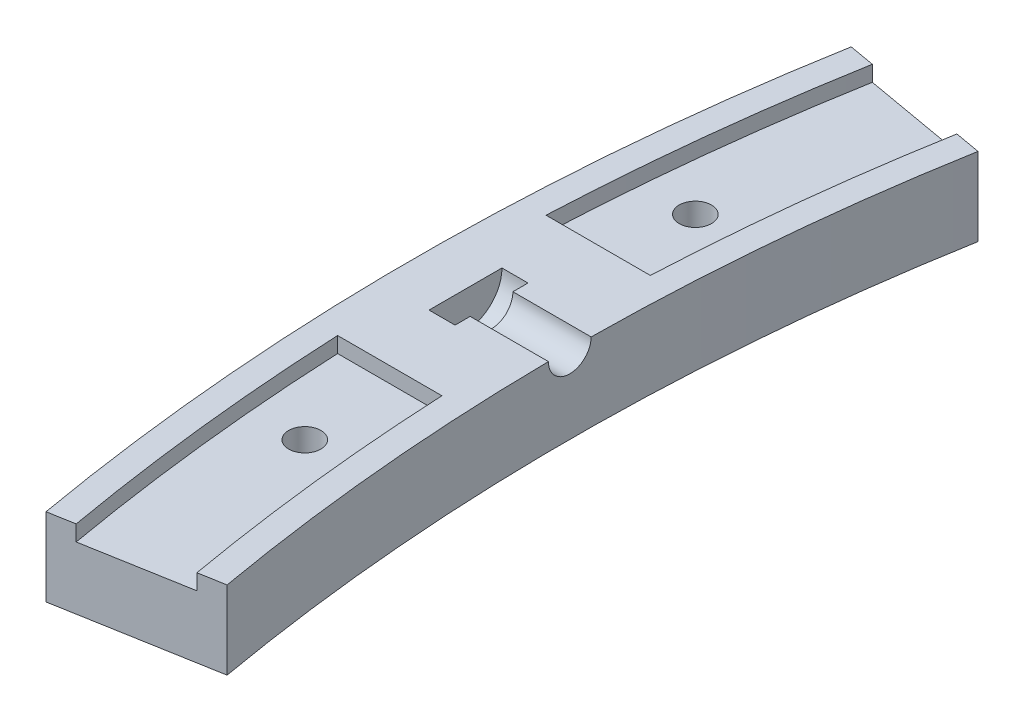
SolidWorks part; units mm, degrees
ref_plane "Front Plane" through (0, 0, 0) normal (0, 0, 1) x (1, 0, 0)
ref_plane "Top Plane" through (0, 0, 0) normal (0, 1, 0) x (1, 0, 0)
ref_plane "Right Plane" through (0, 0, 0) normal (1, 0, 0) x (0, 0, -1)
sketch "Sketch1" plane through (0, 0, 0) normal (0, 1, 0) x (1, 0, 0)
  line L0 (0, 0) -> (-219.1197, -38.6367) construction
  line L1 (0, 0) -> (-219.1197, 38.6367) construction
  line L2 (0, 0) -> (-215, 0) construction
  line L3 (-219.1197, 38.6367) -> (-204.3476, 36.032)
  line L4 (-204.3476, -36.032) -> (-219.1197, -38.6367)
  arc A0 (-216.6577, 38.2026) -> (-216.6577, -38.2026) centre (0, 0) ccw construction
  arc A1 (-206.8096, 36.4661) -> (-206.8096, -36.4661) centre (0, 0) ccw construction
  arc A2 (-211.7337, -37.3344) -> (-211.7337, 37.3344) centre (0, 0) cw construction
  arc A3 (-219.1197, 38.6367) -> (-219.1197, -38.6367) centre (0, 0) ccw
  arc A4 (-204.3476, 36.032) -> (-204.3476, -36.032) centre (0, 0) ccw
  dimension "D1" = 220
  dimension "D2" = 210
  dimension "D3" = 5
  dimension "D5" = 2.5
  dimension "D6" = 2.5
  dimension "D4" = 20
extrude "Boss-Extrude1" add sketch "Sketch1" along normal blind 7.5
sketch "Sketch2" plane through (0, 7.5, 0) normal (0, 1, 0) x (1, 0, 0)
  line L2 (0, 0) -> (-215, 0) construction
  line L3 (0, 0) -> (-219.1197, -38.6367) construction
  line L4 (0, 0) -> (-219.1197, 38.6367) construction
  line L5 (0, 0) -> (-210, 0) construction
  line L6 (0, 0) -> (-219.1197, -38.6367) construction
  line L7 (0, 0) -> (-219.1197, 38.6367) construction
  line L8 (0, 10) -> (-222.2752, 10) construction
  line L9 (0, 10) -> (0, -10) construction
  line L10 (0, -10) -> (-222.2752, -10) construction
  line L11 (-216.6577, 38.2026) -> (-206.8096, 36.4661)
  line L12 (-216.6577, -38.2026) -> (-206.8096, -36.4661)
  line L13 (-219.7726, -10) -> (-209.7618, -10)
  line L14 (-209.7618, 10) -> (-219.7726, 10)
  arc A0 (-216.6577, 38.2026) -> (-216.6577, -38.2026) centre (0, 0) ccw construction
  arc A1 (-206.8096, 36.4661) -> (-206.8096, -36.4661) centre (0, 0) ccw construction
  arc A2 (-216.6577, 38.2026) -> (-216.6577, -38.2026) centre (0, 0) ccw
  arc A3 (-206.8096, 36.4661) -> (-206.8096, -36.4661) centre (0, 0) ccw
  arc A4 (-219.1197, 38.6367) -> (-219.1197, -38.6367) centre (0, 0) ccw construction
  line M2 (-219.1197, -38.6367) -> (-204.3476, -36.032)
  line M4 (-204.3476, 36.032) -> (-219.1197, 38.6367)
  dimension "D1" = 20
extrude "Cut-Extrude1" cut sketch "Sketch2" against normal blind 1.5 contours A3 A2 L14 M4 | A3 L13 A2 M2
ref_plane "Plane1" through (-215, 0, 0) normal (1, 0, 0) x (0, 0, -1)
sketch "Sketch4" plane through (-215, 0, 0) normal (1, 0, 0) x (0, 0, -1)
  line L0 (36.032, 7.5) -> (-36.032, 7.5) construction
  circle A0 centre (0, 7.5) radius 3.5
  dimension "D1" = 7
extrude "Cut-Extrude3" cut sketch "Sketch4" against normal blind 2.5
sketch "Sketch5" plane through (-215, 0, 0) normal (1, 0, 0) x (0, 0, -1)
  line L0 (36.032, 7.5) -> (-36.032, 7.5) construction
  circle A0 centre (0, 7.5) radius 2.05
  dimension "D1" = 4.1
extrude "Cut-Extrude4" cut sketch "Sketch5" along normal through all
sketch "Sketch6" plane through (0, 0, 0) normal (0, -1, 0) x (1, 0, 0)
  line L0 (0, 0) -> (-214.1819, 18.7385) construction
  line L1 (0, 0) -> (-215, 0) construction
  line L2 (0, 0) -> (-215, 0) construction
  line L3 (0, 0) -> (-214.1819, -18.7385) construction
  arc A0 (-211.7337, 37.3344) -> (-211.7337, -37.3344) centre (0, 0) ccw construction
  dimension "D1" = 5
hole_wizard "Ø3.1 (3.1) Diameter Hole1" positions "Sketch7" profile "Sketch8" hole size "Ø3.1" standard "ISO" end condition through all
sketch "Sketch7" plane through (0, 0, 0) normal (0, -1, 0) x (-1, 0, 0)
  point P0 (214.1819, -18.7385)
  point P3 (214.1819, 18.7385)
sketch "Sketch8" plane through (-214.1819, 0, 18.7385) normal (1, 0, 0) x (0, 0, -1)
  line L0 (0, 0) -> (0, 7.6156)
  line L1 (0, 7.6156) -> (1.55, 7.6156)
  line L2 (1.55, 7.6156) -> (1.55, 0)
  line L5 (1.55, 0) -> (0, 0)
  line L11 (0, -6.35) -> (0, 107.95) construction
  dimension "Thru Hole Dia." = 3.1
  dimension "Thru Hole Depth" = 7.6156
